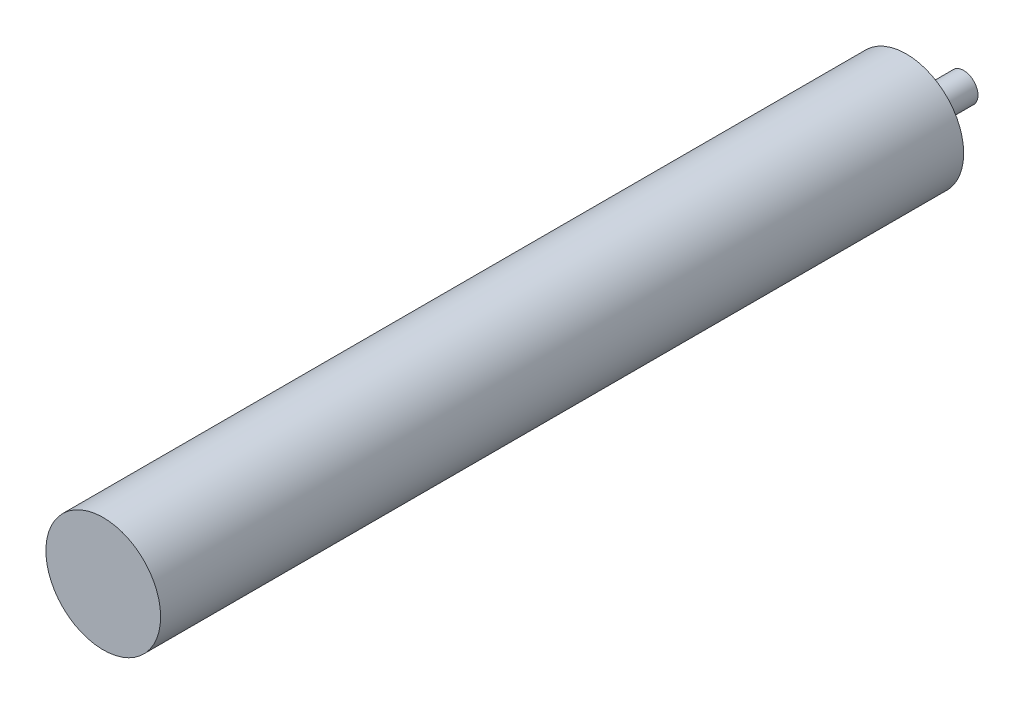
SolidWorks part; units mm, degrees
ref_plane "Ön Düzlem" through (0, 0, 0) normal (0, 0, 1) x (1, 0, 0)
ref_plane "Üst Düzlem" through (0, 0, 0) normal (0, 1, 0) x (1, 0, 0)
ref_plane "Sağ Düzlem" through (0, 0, 0) normal (1, 0, 0) x (0, 0, -1)
sketch "Çizim2" plane through (0, 0, 0) normal (0, 0, 1) x (1, 0, 0)
  circle A0 centre (0, 0) radius 0.5
  dimension "D1" = 1
extrude "Yükseklik-Ekstrüzyon1" add sketch "Çizim2" along normal blind 2
sketch "Çizim3" plane through (0, 0, 2) normal (0, 0, 1) x (1, 0, 0)
  circle A0 centre (0, 0) radius 2
  dimension "D1" = 4
extrude "Yükseklik-Ekstrüzyon2" add sketch "Çizim3" along normal blind 28
